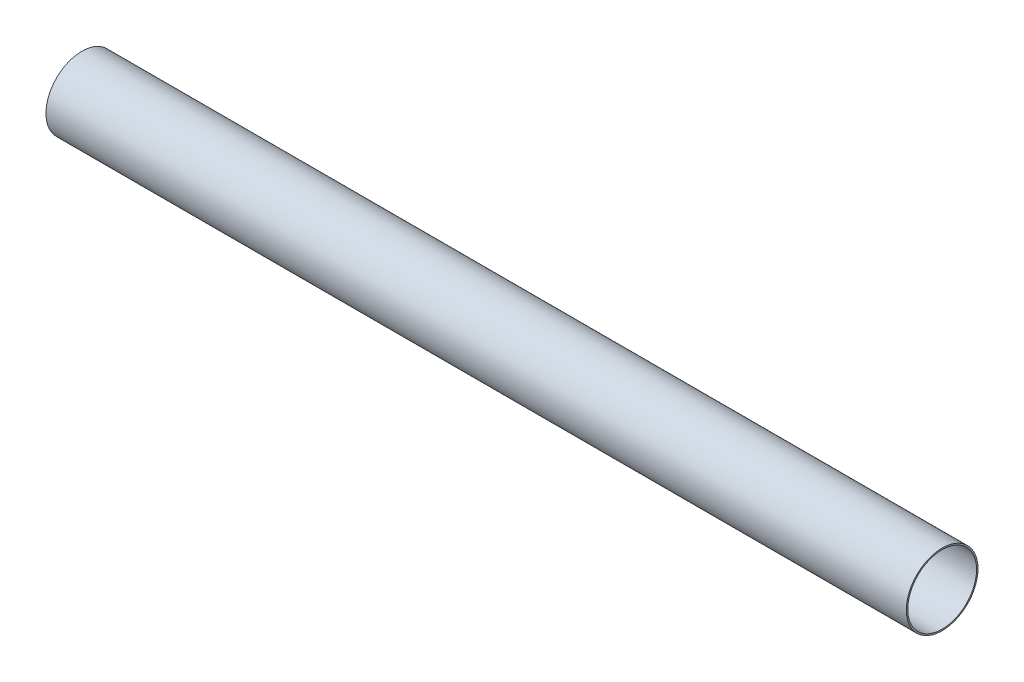
SolidWorks part; units mm, degrees
material "Copper"
ref_plane "Front Plane" through (0, 0, 0) normal (0, 0, 1) x (1, 0, 0)
ref_plane "Top Plane" through (0, 0, 0) normal (0, 1, 0) x (1, 0, 0)
ref_plane "Right Plane" through (0, 0, 0) normal (1, 0, 0) x (0, 0, -1)
sketch "Sketch1" plane through (0, 0, 0) normal (1, 0, 0) x (0, 0, -1)
  circle A4 centre (0, 0) radius 2.88
  circle A6 centre (0, 0) radius 3
  dimension "D1" = 5.76
  dimension "D2" = 6
extrude "Boss-Extrude1" add sketch "Sketch1" along normal blind 72
